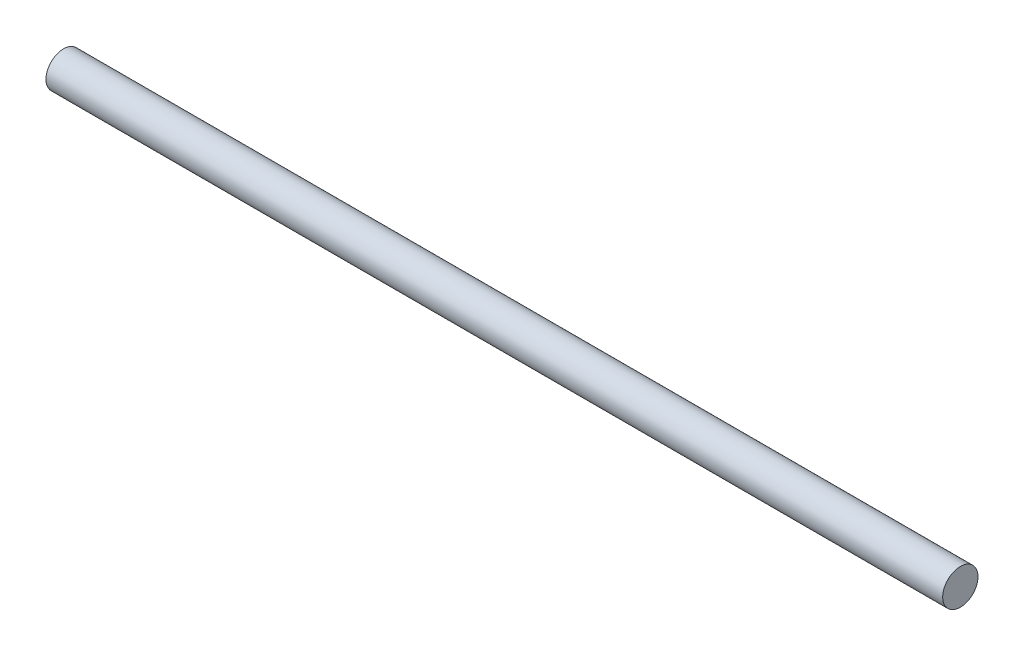
SolidWorks part; units mm, degrees
ref_plane "Front Plane" through (0, 0, 0) normal (1, 0, 0) x (0, 1, 0)
ref_plane "Top Plane" through (0, 0, 0) normal (0, 0, 1) x (0, 1, 0)
ref_plane "Right Plane" through (0, 0, 0) normal (0, 1, 0) x (-1, 0, 0)
sketch "Sketch1" plane through (0, 0, 0) normal (1, 0, 0) x (0, 1, 0)
  circle A0 centre (-26.2949, 30.0418) radius 6
  dimension "D1" = 12
extrude "Boss-Extrude1" add sketch "Sketch1" along normal blind 304.54
